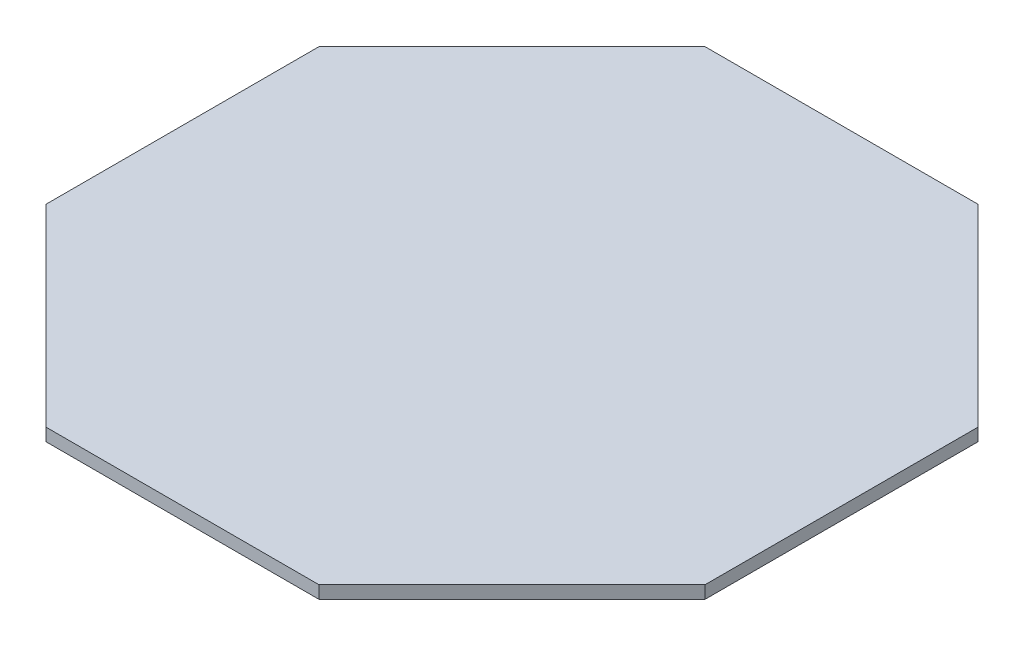
SolidWorks part; units mm, degrees
ref_plane "Front Plane" through (0, 0, 0) normal (0, 0, 1) x (1, 0, 0)
ref_plane "Top Plane" through (0, 0, 0) normal (0, 1, 0) x (1, 0, 0)
ref_plane "Right Plane" through (0, 0, 0) normal (1, 0, 0) x (0, 0, -1)
sketch "Sketch6" plane through (0, 0, 0) normal (0, 1, 0) x (1, 0, 0)
  line L1 (78, 32.3087) -> (32.3087, 78)
  line L2 (32.3087, 78) -> (-32.3087, 78)
  line L3 (-32.3087, 78) -> (-78, 32.3087)
  line L4 (-78, 32.3087) -> (-78, -32.3087)
  line L5 (-78, -32.3087) -> (-32.3087, -78)
  line L6 (-32.3087, -78) -> (32.3087, -78)
  line L7 (32.3087, -78) -> (78, -32.3087)
  line L8 (78, -32.3087) -> (78, 32.3087)
  circle A0 centre (0, 0) radius 78 construction
extrude "Boss-Extrude5" add sketch "Sketch6" against normal blind 3
